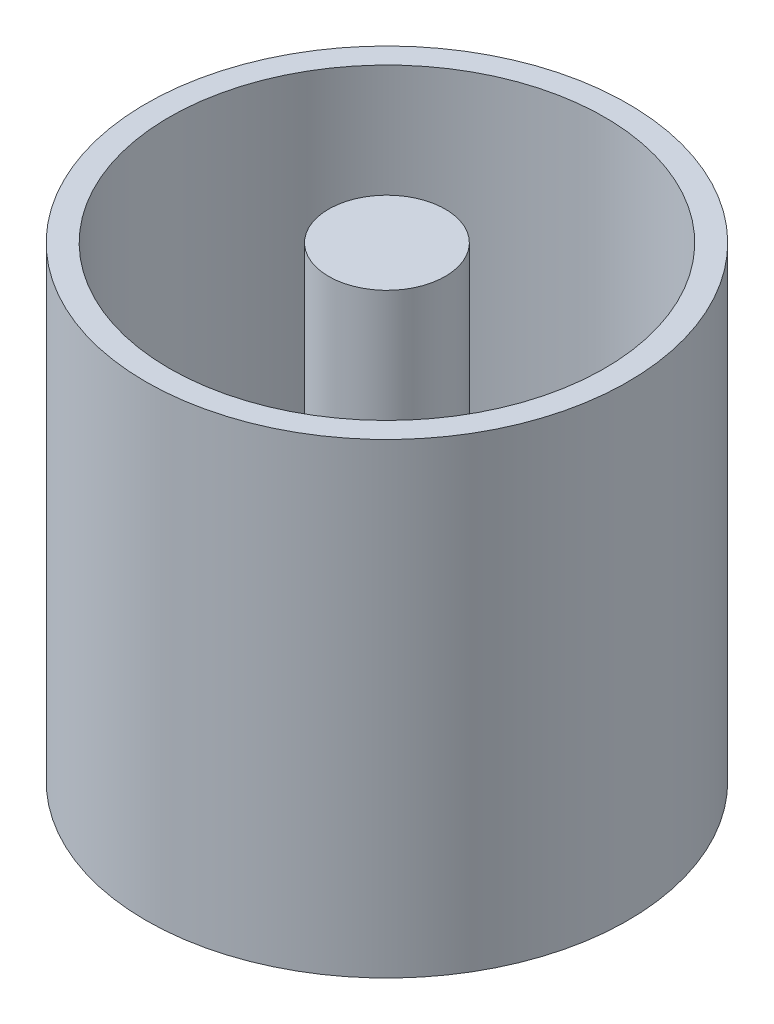
SolidWorks part; units mm, degrees
ref_plane "Front Plane" through (0, 0, 0) normal (0, 0, 1) x (1, 0, 0)
ref_plane "Top Plane" through (0, 0, 0) normal (0, 1, 0) x (1, 0, 0)
ref_plane "Right Plane" through (0, 0, 0) normal (1, 0, 0) x (0, 0, -1)
sketch "Sketch1" plane through (0, 0, 0) normal (0, 1, 0) x (1, 0, 0)
  circle A0 centre (0, 0) radius 15.5
  dimension "D1" = 31
extrude "Boss-Extrude1" add sketch "Sketch1" along normal blind 30
sketch "Sketch2" plane through (0, 30, 0) normal (0, 1, 0) x (1, 0, 0)
  circle A0 centre (0, 0) radius 14
  dimension "D1" = 28
extrude "Cut-Extrude1" cut sketch "Sketch2" against normal blind 27
sketch "Sketch3" plane through (0, 0, 0) normal (0, -1, 0) x (1, 0, 0)
  circle A0 centre (-9, 0) radius 1
  circle A1 centre (-12.5, 0) radius 1
  dimension "D1" = 2
  dimension "D2" = 2
  dimension "D3" = 9
  dimension "D4" = 12.5
extrude "Cut-Extrude2" cut sketch "Sketch3" against normal blind 10
sketch "Sketch4" plane through (0, 3, 0) normal (0, 1, 0) x (1, 0, 0)
  circle A0 centre (0, 0) radius 3.75
  dimension "D1" = 7.5
extrude "Boss-Extrude2" add sketch "Sketch4" along normal blind 27
